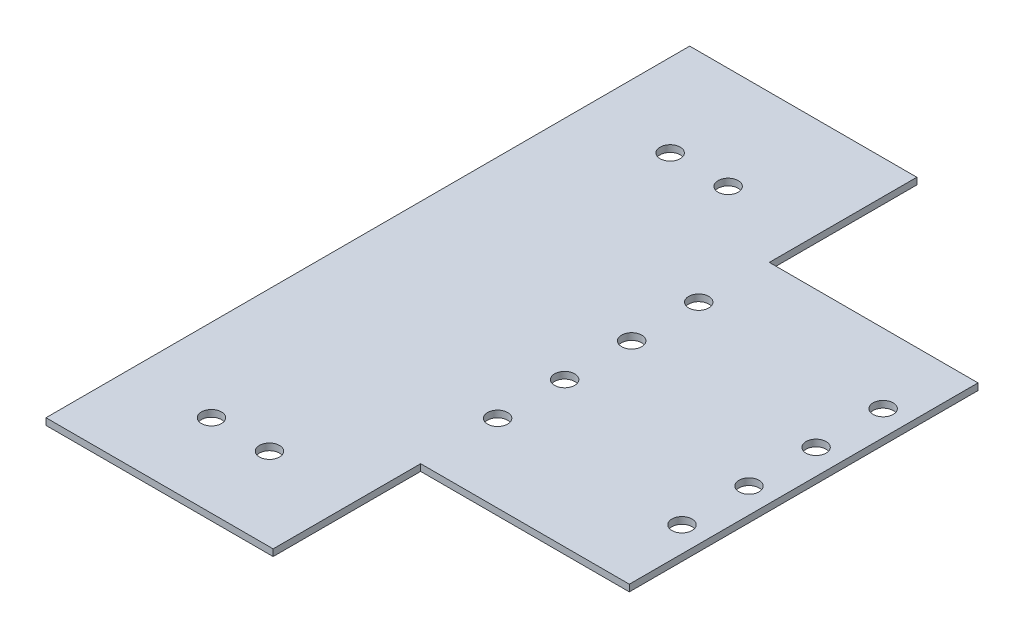
SolidWorks part; units mm, degrees
ref_plane "Спереди" through (0, 0, 0) normal (0, 0, 1) x (1, 0, 0)
ref_plane "Сверху" through (0, 0, 0) normal (0, 1, 0) x (1, 0, 0)
ref_plane "Справа" through (0, 0, 0) normal (1, 0, 0) x (0, 0, -1)
sketch "Эскиз1" plane through (0, 0, 0) normal (0, 1, 0) x (1, 0, 0)
  line L5 (49.9338, 26) -> (18.8099, 26)
  line L6 (49.9338, 26) -> (49.9338, -26)
  line L7 (49.9338, -26) -> (18.8099, -26)
  line L8 (-48.9591, 48) -> (15, 48)
  line L9 (-48.9591, 48) -> (-48.9591, -48)
  line L10 (-50, 0) -> (49.9338, 0) construction
  line L11 (-48.9591, -48) -> (15, -48)
  line L12 (-45.2656, -36.9305) -> (-45.2656, -25.3095)
  line L13 (-45.2656, 36.9305) -> (-27.3726, 36.9305)
  line L14 (-45.2656, 36.9305) -> (-45.2656, 25.3095)
  line L15 (-45.2656, 25.3095) -> (-27.3726, 25.3095)
  line L16 (-27.3726, 36.9305) -> (-27.3726, 25.3095)
  line L21 (-45.2656, -25.3095) -> (-27.3726, -25.3095)
  line L22 (-27.3726, -36.9305) -> (-27.3726, -25.3095)
  line L23 (-45.2656, -36.9305) -> (-27.3726, -36.9305)
  line L24 (-15.0662, -48) -> (20.6445, -48) construction
  line L27 (15, -48) -> (18.8099, -48)
  line L28 (18.8099, -26) -> (18.8099, -48)
  line L29 (15, 48) -> (18.8099, 48)
  line L30 (18.8099, 26) -> (18.8099, 48)
  line L31 (19.8099, 48) -> (19.8099, 26) construction
  line L32 (18.0113, 27.0025) -> (47.8563, 27.0025) construction
  dimension "D1" = 1
  dimension "D2" = 1.0025
extrude "Бобышка-Вытянуть1" add sketch "Эскиз1" along normal blind 1
sketch "Эскиз2" plane through (0, 1, 0) normal (0, 1, 0) x (1, 0, 0)
  circle A0 centre (46.1838, -14.4) radius 1.5
  circle A1 centre (18.6838, -14.4) radius 1.5
  circle A2 centre (18.6838, -4.4) radius 1.5
  circle A3 centre (46.1838, -4.4) radius 1.5
  circle A4 centre (18.6838, 5.6) radius 1.5
  circle A5 centre (46.1838, 5.6) radius 1.5
  circle A6 centre (18.6838, 15.6) radius 1.5
  circle A7 centre (46.1838, 15.6) radius 1.5
  dimension "D1" = 4
extrude "Вырез-Вытянуть1" cut sketch "Эскиз2" against normal blind 10
sketch "Эскиз3" plane through (0, 1, 0) normal (0, 1, 0) x (1, 0, 0)
  circle A0 centre (5.9236, 32.747) radius 1.5
  circle A1 centre (-2.7264, 32.747) radius 1.5
  circle A2 centre (-2.7264, -35.6602) radius 1.5
  circle A3 centre (5.9236, -35.6602) radius 1.5
extrude "Вырез-Вытянуть2" cut sketch "Эскиз3" against normal blind 10
sketch "Эскиз4" plane through (0, 0, 0) normal (0, -1, 0) x (1, 0, 0)
  line L0 (-15.0662, -48) -> (-48.9591, -48)
  line L2 (-48.9591, -48) -> (-48.9591, 48)
  line L3 (-48.9591, 48) -> (-15.0662, 48)
  line L5 (-48.9591, 48) -> (18.8099, 48) construction
  line L6 (-15.0662, -48) -> (-15.0662, 48)
  dimension "D2" = 0
extrude "Вырез-Вытянуть3" cut sketch "Эскиз4" against normal blind 10
